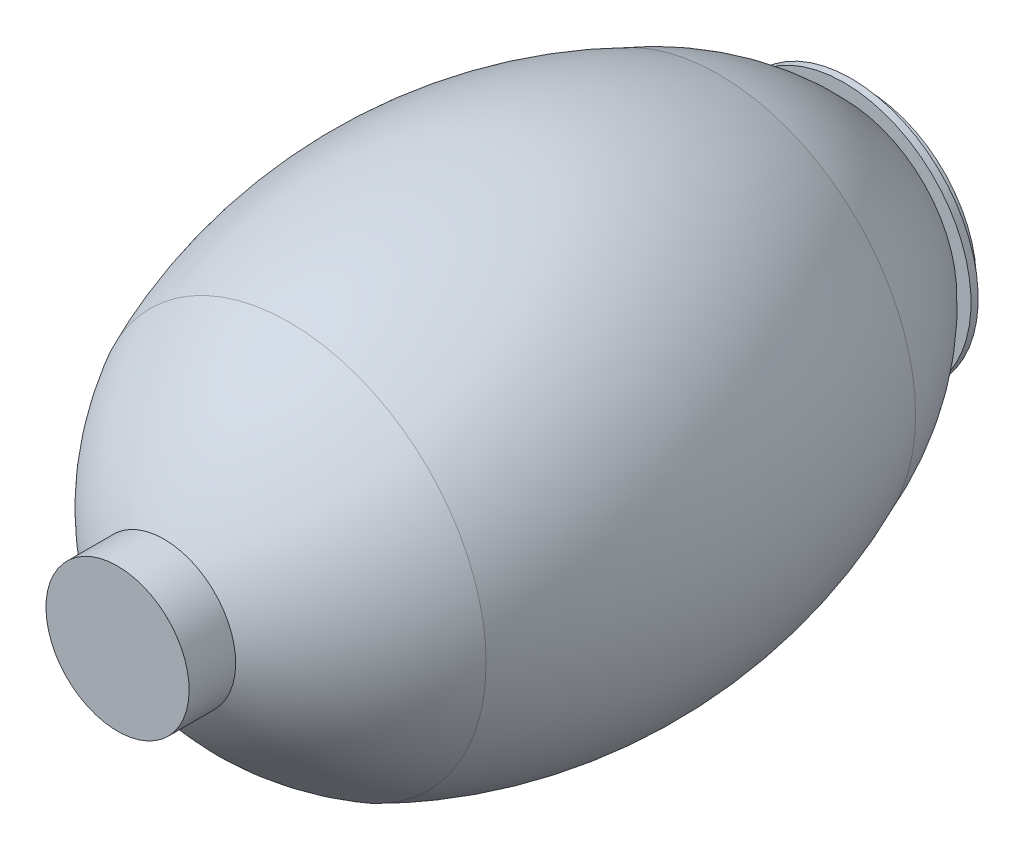
SolidWorks part; units mm, degrees
ref_plane "Front Plane" through (0, 0, 0) normal (0, 0, 1) x (1, 0, 0)
ref_plane "Top Plane" through (0, 0, 0) normal (0, 1, 0) x (1, 0, 0)
ref_plane "Right Plane" through (0, 0, 0) normal (1, 0, 0) x (0, 0, -1)
sketch "Sketch1" plane through (0, 0, 0) normal (1, 0, 0) x (0, 0, -1)
  line L0 (0, 0) -> (0, 20)
  line L1 (0, 20) -> (13, 20)
  line L2 (203, 31.5) -> (203, 35.5)
  line L3 (203, 35.5) -> (205, 35.5)
  line L4 (205, 35.5) -> (205, 31)
  line L5 (205, 31) -> (209, 31)
  line L6 (209, 31) -> (209, 0)
  line L7 (209, 0) -> (0, 0)
  line L8 (108, 67.5) -> (176.7271, 67.5) construction
  line L9 (108, 67.5) -> (108, 0) construction
  arc A0 (13, 20) -> (48, 55) centre (91.6862, -23.6862) cw
  arc A1 (48, 55) -> (168, 55) centre (108, -82.75) cw
  arc A2 (168, 55) -> (203, 31.5) centre (136.7263, -29.3917) cw
  point P17 (0, 0)
  point P18 (0, 0)
  point P20 (202.5642, 20.7138)
  point P21 (203, 28.2754)
  dimension "D1" = 67.5
  dimension "D13" = 90
  dimension "D14" = 90
  dimension "D2" = 55
  dimension "D3" = 120
  dimension "D4" = 13
  dimension "D5" = 31.5
  dimension "D6" = 20
  dimension "D7" = 35
  dimension "D8" = 35
  dimension "D9" = 35.5
  dimension "D10" = 2
  dimension "D11" = 4
  dimension "D12" = 31
revolve "Revolve1" add sketch "Sketch1" angle 360 about L7
